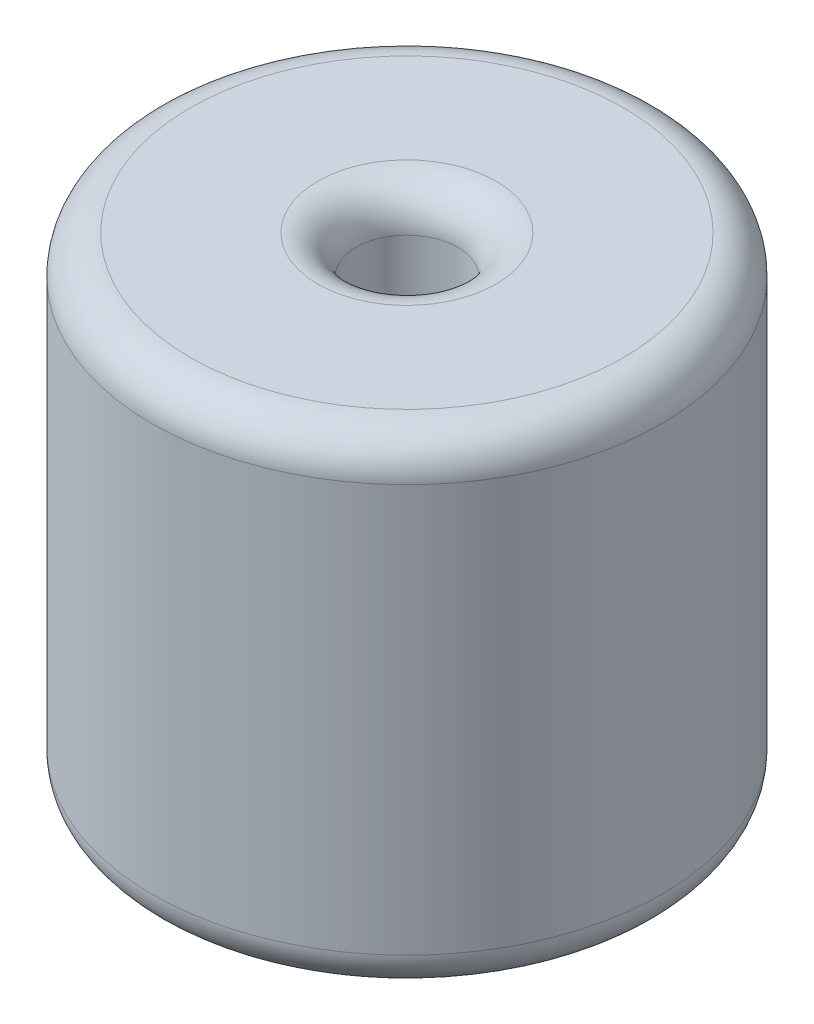
SolidWorks part; units mm, degrees
ref_plane "Front" through (0, 0, 0) normal (0, 0, 1) x (1, 0, 0)
ref_plane "Top" through (0, 0, 0) normal (0, 1, 0) x (1, 0, 0)
ref_plane "Right" through (0, 0, 0) normal (1, 0, 0) x (0, 0, -1)
sketch "Sketch1" plane through (0, 0, 0) normal (0, 1, 0) x (1, 0, 0)
  circle A0 centre (0, 0) radius 20
  dimension "D1" = 40
extrude "Boss-Extrude1" add sketch "Sketch1" along normal blind 38
sketch "Sketch4" plane through (0, 38, 0) normal (0, 1, 0) x (1, 0, 0)
  circle A0 centre (0, 0) radius 4
  dimension "D1" = 8
extrude "Cut-Extrude1" cut sketch "Sketch4" against normal through all
fillet "Fillet1" radius 3 4 edges at (0, 0, 20) (0, 0, 4) (0, 38, 20) (0, 38, 4)
